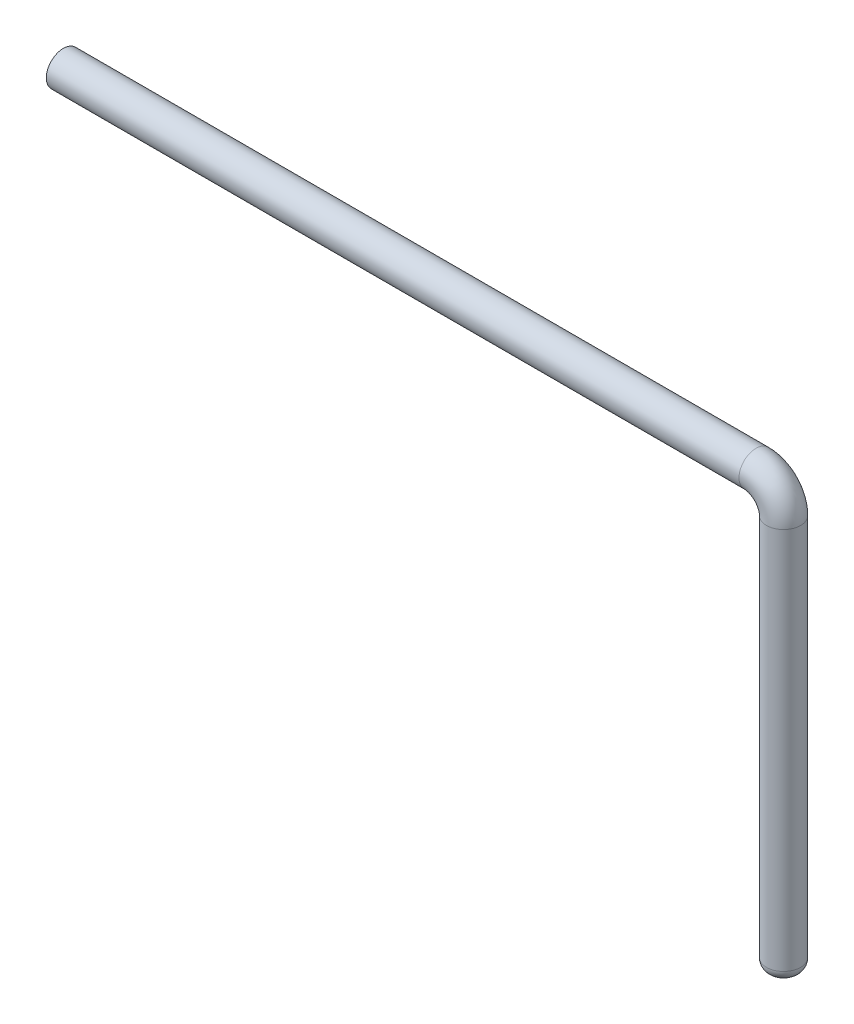
SolidWorks part; units mm, degrees
ref_plane "前视基准面" through (0, 0, 0) normal (0, 0, 1) x (1, 0, 0)
ref_plane "上视基准面" through (0, 0, 0) normal (0, 1, 0) x (1, 0, 0)
ref_plane "右视基准面" through (0, 0, 0) normal (1, 0, 0) x (0, 0, -1)
sketch "草图1" plane through (0, 0, 0) normal (0, 0, 1) x (1, 0, 0)
  line L0 (51.4229, 34.0648) -> (64.0029, 34.0648)
  line L1 (64.5029, 33.5648) -> (64.5029, 26.4148)
  arc A0 (64.5029, 33.5648) -> (64.0029, 34.0648) centre (64.0029, 33.5648) ccw
  dimension "D1" = 0.5
sweep "扫描1" add path "草图1" circular profile diameter 0.62 parameters "D3"=0.62
fillet "圆角1" radius 0.2 1 edges at (64.5029, 26.4148, 0.31)
